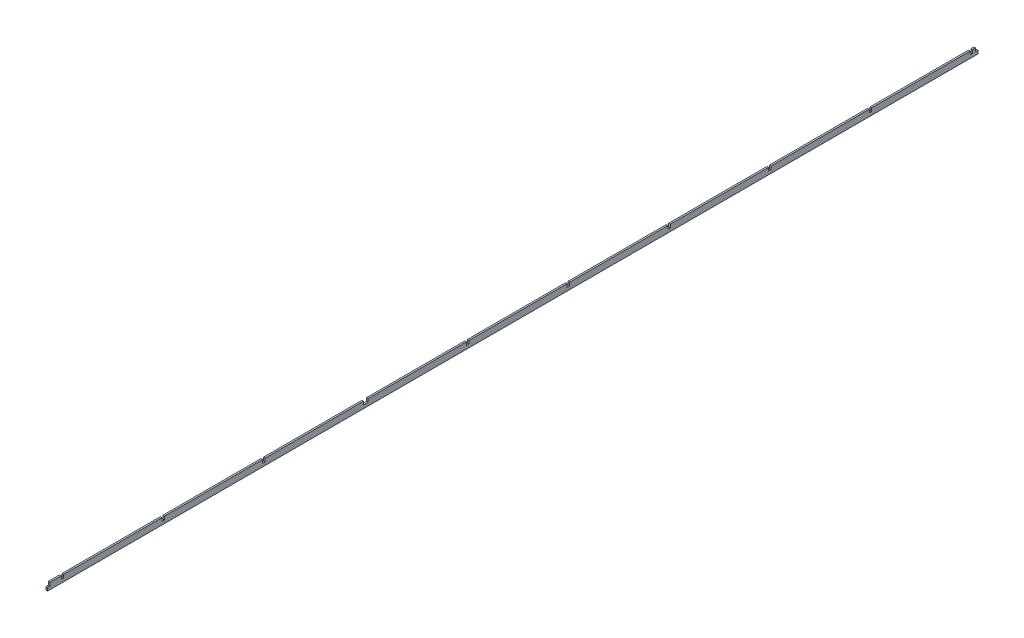
SolidWorks part; units mm, degrees
material "轻木"
ref_plane "前视基准面" through (0, 0, 0) normal (0, 0, 1) x (1, 0, 0)
ref_plane "上视基准面" through (0, 0, 0) normal (0, 1, 0) x (1, 0, 0)
ref_plane "右视基准面" through (0, 0, 0) normal (1, 0, 0) x (0, 0, -1)
other "Configuration Table"
sketch "草图1" plane through (0, 0, -111.99) normal (0, 0, 1) x (1, 0, 0)
  line L1 (87.0376, -2.9396) -> (85.0376, -2.9396)
  line L2 (87.0376, -2.9396) -> (87.0376, 5.0604)
  line L3 (87.0376, 5.0604) -> (85.0376, 5.0604)
  line L4 (85.0376, -2.9396) -> (85.0376, 5.0604)
  dimension "D1" = 8
  dimension "D2" = 2
extrude "凸台-拉伸1" add sketch "草图1" along normal blind 1155
sketch "草图2" plane through (87.0376, 0, 0) normal (1, 0, 0) x (0, 0, -1)
  line L1 (111.99, 5.0604) -> (108.99, 5.0604)
  line L2 (111.99, 5.0604) -> (111.99, 1.0604)
  line L3 (111.99, 1.0604) -> (108.99, 1.0604)
  line L4 (108.99, 5.0604) -> (108.99, 1.0604)
  line L5 (108.99, -2.1592) -> (108.99, -2.9396) construction
  line L6 (-1043.01, 5.0604) -> (111.99, 5.0604) construction
  line L7 (111.99, -0.9531) -> (111.99, 24.194) construction
  line L8 (104.99, -0.9531) -> (104.99, 25.7817) construction
  line L13 (104.99, 5.0604) -> (101.99, 5.0604)
  line L38 (104.99, 5.0604) -> (104.99, 1.0194)
  line L55 (-20.01, 5.0604) -> (-23.01, 5.0604)
  line L61 (104.99, 1.0194) -> (101.99, 1.0194)
  line L62 (-20.01, 5.0604) -> (-20.01, 1.0194)
  line L63 (-20.01, 1.0194) -> (-23.01, 1.0194)
  line L64 (101.99, 5.0604) -> (101.99, 1.0194)
  line L65 (-23.01, 5.0604) -> (-23.01, 1.0194)
  line L66 (104.99, 5.0604) -> (-20.01, 5.0604) construction
  line L67 (-145.01, 5.0604) -> (-148.01, 5.0604)
  line L68 (-145.01, 5.0604) -> (-145.01, 1.0194)
  line L69 (-145.01, 1.0194) -> (-148.01, 1.0194)
  line L70 (-148.01, 5.0604) -> (-148.01, 1.0194)
  line L71 (-270.01, 5.0604) -> (-273.01, 5.0604)
  line L72 (-270.01, 5.0604) -> (-270.01, 1.0194)
  line L73 (-270.01, 1.0194) -> (-273.01, 1.0194)
  line L74 (-273.01, 5.0604) -> (-273.01, 1.0194)
  line L75 (-395.01, 5.0604) -> (-398.01, 5.0604)
  line L76 (-395.01, 5.0604) -> (-395.01, 1.0194)
  line L77 (-395.01, 1.0194) -> (-398.01, 1.0194)
  line L78 (-398.01, 5.0604) -> (-398.01, 1.0194)
  line L79 (-520.01, 5.0604) -> (-523.01, 5.0604)
  line L80 (-520.01, 5.0604) -> (-520.01, 1.0194)
  line L81 (-520.01, 1.0194) -> (-523.01, 1.0194)
  line L82 (-523.01, 5.0604) -> (-523.01, 1.0194)
  line L83 (-645.01, 5.0604) -> (-648.01, 5.0604)
  line L84 (-645.01, 5.0604) -> (-645.01, 1.0194)
  line L85 (-645.01, 1.0194) -> (-648.01, 1.0194)
  line L86 (-648.01, 5.0604) -> (-648.01, 1.0194)
  line L87 (-773.01, 5.0604) -> (-773.01, 1.0194)
  line L88 (-648.01, 5.0604) -> (-651.01, 5.0604)
  line L89 (-648.01, 5.0604) -> (-648.01, 1.0194)
  line L90 (-648.01, 1.0194) -> (-651.01, 1.0194)
  line L91 (-651.01, 5.0604) -> (-651.01, 1.0194)
  line L92 (-773.01, 5.0604) -> (-776.01, 5.0604)
  line L93 (-773.01, 5.0604) -> (-773.01, 1.0194)
  line L94 (-773.01, 1.0194) -> (-776.01, 1.0194)
  line L95 (-776.01, 5.0604) -> (-776.01, 1.0194)
  line L96 (-898.01, 5.0604) -> (-898.01, 1.0194)
  line L97 (-898.01, 5.0604) -> (-901.01, 5.0604)
  line L98 (-898.01, 5.0604) -> (-898.01, 1.0194)
  line L99 (-898.01, 1.0194) -> (-901.01, 1.0194)
  line L100 (-901.01, 5.0604) -> (-901.01, 1.0194)
  line L101 (-1023.01, 5.0604) -> (-1023.01, 1.0194)
  line L102 (-1023.01, 5.0604) -> (-1026.01, 5.0604)
  line L103 (-1023.01, 5.0604) -> (-1023.01, 1.0194)
  line L104 (-1023.01, 1.0194) -> (-1026.01, 1.0194)
  line L105 (-1026.01, 5.0604) -> (-1026.01, 1.0194)
  line L106 (-648.01, 5.0604) -> (-773.01, 5.0604) construction
  line L108 (-1040.01, 3.6429) -> (-1040.01, 0.5929) construction
  line L109 (-1043.01, -2.9396) -> (-1043.01, 5.0604) construction
  line L110 (-1040.01, 1.0194) -> (-1043.01, 1.0194)
  line L111 (-1040.01, 1.0194) -> (-1040.01, 5.0604)
  line L112 (-1040.01, 5.0604) -> (-1043.01, 5.0604)
  line L113 (-1043.01, 1.0194) -> (-1043.01, 5.0604)
  line M5 (111.99, -2.9396) -> (111.99, 5.0604)
  line M6 (111.99, 5.0604) -> (-1043.01, 5.0604)
  line M7 (-1043.01, 5.0604) -> (-1043.01, -2.9396)
  dimension "D1" = 125
  dimension "D2" = 7
  dimension "D4" = 4
  dimension "D5" = 4
  dimension "D3" = 125
extrude "切除-拉伸1" cut sketch "草图2" against normal through all contours L110 L111 M6 M7 | L105 L104 L101 M6 | L100 L99 L96 M6 | L95 L94 L87 M6 | L91 L90 L86 M6 | L86 L85 L84 M6 | L82 L81 L80 M6 | L78 L77 L76 M6 | L74 L73 L72 M6 | L70 L69 L68 M6 | L65 L63 L62 M6 | L64 L61 L38 M6 | L4 L3 M6 M5
